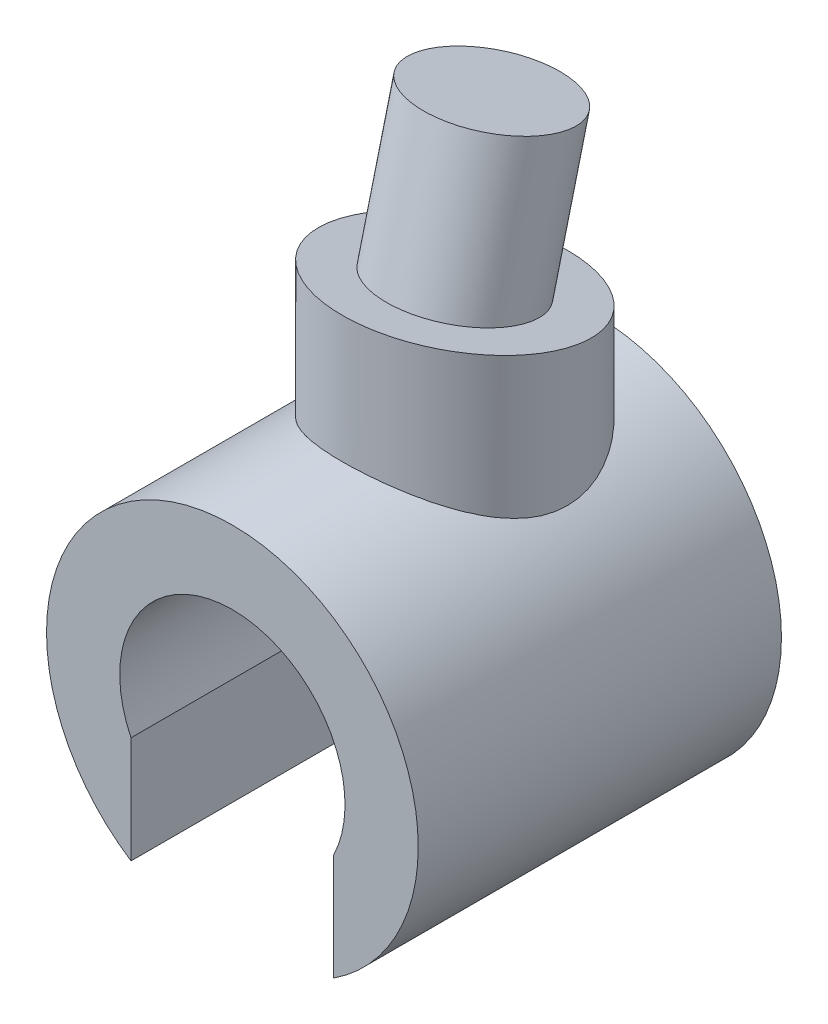
SolidWorks part; units mm, degrees
ref_plane "Alzado" through (0, 0, 0) normal (0, 0, 1) x (1, 0, 0)
ref_plane "Planta" through (0, 0, 0) normal (0, 1, 0) x (1, 0, 0)
ref_plane "Vista lateral" through (0, 0, 0) normal (1, 0, 0) x (0, 0, -1)
sketch "Croquis3" plane through (0, 0, 0) normal (0, 0, 1) x (1, 0, 0)
  line L0 (-3.6, -1.7436) -> (-3.6, -5.5317)
  line L1 (3.6, -1.7436) -> (3.6, -5.5317)
  arc A0 (3.6, -5.5317) -> (-3.6, -5.5317) centre (0, 0) ccw
  arc A1 (3.6, -1.7436) -> (-3.6, -1.7436) centre (0, 0) ccw
  dimension "D1" = 13.2
  dimension "D2" = 8
  dimension "D3" = 7.2
  dimension "D4" = 3.6
extrude "Saliente-Extruir1" add sketch "Croquis3" along normal mid plane 12.9
sketch "Croquis4" plane through (0, 0, 0) normal (1, 0, 0) x (0, 0, -1)
  line L0 (1.45, 4.2964) -> (1.45, 11.1) construction
  line L2 (1.45, 11.1) -> (5.45, 11.1)
  line L3 (5.45, 11.1) -> (5.45, 4.2964)
  line L4 (5.45, 4.2964) -> (1.45, 4.2964)
  line L5 (6.45, -5.5317) -> (6.45, 6.6) construction
  line L6 (1.45, 4.2964) -> (1.45, 11.1)
  line L7 (6.45, 6.6) -> (-6.45, 6.6) construction
  dimension "D1" = 4.5
  dimension "D2" = 8
  dimension "D3" = 1
revolve "Revolución5" add sketch "Croquis4" angle 360 about L0
sketch "Croquis5" plane through (0, 0, 0) normal (1, 0, 0) x (0, 0, -1)
  line L0 (-2.55, 11.1) -> (5.45, 9.1)
  line L1 (5.45, 4.2964) -> (5.45, 11.1) construction
  line L2 (5.45, 9.1) -> (5.45, 11.1)
  line L3 (5.45, 11.1) -> (-2.55, 11.1)
  dimension "D1" = 2
extrude "Cortar-Extruir1" cut sketch "Croquis5" against normal through all both and the other way through all
sketch "Croquis6" plane through (0, 9.8471, -2.4618) normal (0, 0.9701, -0.2425) x (1, 0, 0)
  circle A0 centre (0, -1.0429) radius 2.5
  dimension "D1" = 5
extrude "Saliente-Extruir2" add sketch "Croquis6" along normal blind 5.4
